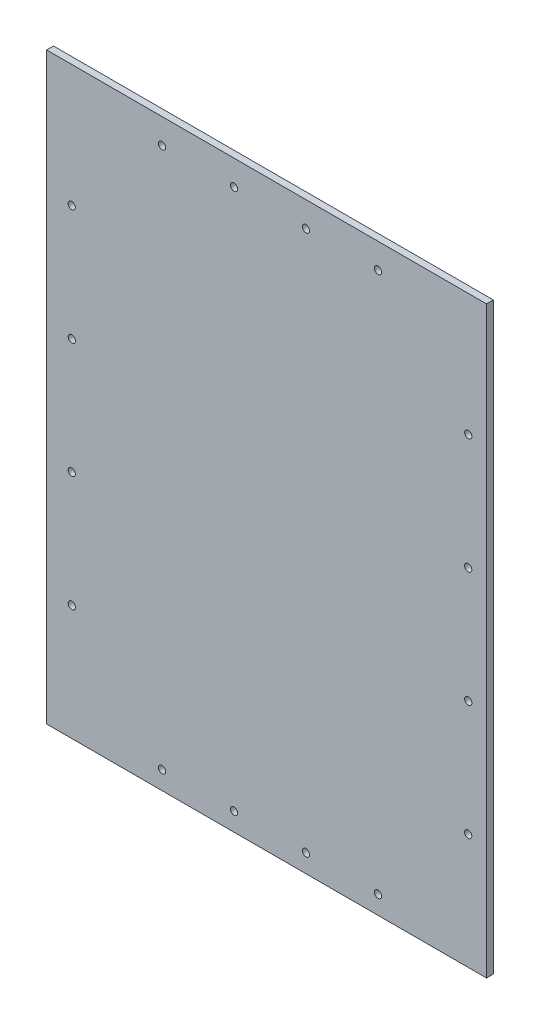
SolidWorks part; units mm, degrees
ref_plane "前基準面" through (0, 0, 0) normal (0, 0, 1) x (1, 0, 0)
ref_plane "上基準面" through (0, 0, 0) normal (0, 1, 0) x (1, 0, 0)
ref_plane "右基準面" through (0, 0, 0) normal (1, 0, 0) x (0, 0, -1)
sketch "草圖1" plane through (0, 0, 0) normal (0, 0, 1) x (1, 0, 0)
  line L1 (152.775, -202.775) -> (-152.775, -202.775)
  line L2 (152.775, -202.775) -> (152.775, 202.775)
  line L3 (152.775, 202.775) -> (-152.775, 202.775)
  line L4 (-152.775, -202.775) -> (-152.775, 202.775)
  line L5 (152.775, -202.775) -> (-152.775, 202.775) construction
  line L6 (152.775, 202.775) -> (-152.775, -202.775) construction
  point P0 (0, 0)
  dimension "D1" = 305.55
  dimension "D2" = 405.55
extrude "填料-伸長1" add sketch "草圖1" along normal blind 4.75
sketch "草圖3" plane through (0, 0, 4.75) normal (0, 0, 1) x (1, 0, 0)
  line L0 (152.775, 202.775) -> (140.075, 202.775) construction
  line L1 (152.775, 202.775) -> (-152.775, 202.775) construction
  line L2 (140.075, 202.775) -> (140.075, 198.025) construction
  line L3 (140.075, 198.025) -> (140.075, 117.865) construction
  line L4 (140.075, 117.865) -> (140.075, 37.705) construction
  line L5 (140.075, 37.705) -> (140.075, -42.455) construction
  line L6 (140.075, -42.455) -> (140.075, -122.615) construction
  circle A0 centre (140.075, 37.705) radius 2.5
  circle A1 centre (140.075, 117.865) radius 2.5
  circle A2 centre (140.075, -42.455) radius 2.5
  circle A3 centre (140.075, -122.615) radius 2.5
  dimension "D7" = 5
  dimension "D8" = 5
  dimension "D9" = 5
  dimension "D10" = 5
  dimension "D1" = 12.7
  dimension "D2" = 4.75
  dimension "D3" = 80.16
  dimension "D4" = 80.16
  dimension "D5" = 80.16
  dimension "D6" = 80.16
extrude "除料-伸長1" cut sketch "草圖3" against normal blind 10
sketch "草圖5" plane through (0, 0, 4.75) normal (0, 0, 1) x (1, 0, 0)
  line L0 (-152.775, 202.775) -> (-148.025, 202.775) construction
  line L1 (152.775, 202.775) -> (-152.775, 202.775) construction
  line L2 (-148.025, 202.775) -> (-135.325, 202.775) construction
  line L3 (-135.325, 202.775) -> (-135.325, 198.025) construction
  line L4 (-135.325, 198.025) -> (-135.325, 117.865) construction
  line L5 (-135.325, 117.865) -> (-135.325, 37.705) construction
  line L6 (-135.325, 37.705) -> (-135.325, -42.455) construction
  line L7 (-135.325, -42.455) -> (-135.325, -122.615) construction
  circle A0 centre (-135.325, -122.615) radius 2.5
  circle A1 centre (-135.325, -42.455) radius 2.5
  circle A2 centre (-135.325, 37.705) radius 2.5
  circle A3 centre (-135.325, 117.865) radius 2.5
  dimension "D8" = 5
  dimension "D9" = 5
  dimension "D10" = 5
  dimension "D11" = 5
  dimension "D1" = 4.75
  dimension "D2" = 12.7
  dimension "D3" = 4.75
  dimension "D4" = 80.16
  dimension "D5" = 80.16
  dimension "D6" = 80.16
  dimension "D7" = 80.16
extrude "除料-伸長3" cut sketch "草圖5" against normal blind 10
sketch "草圖6" plane through (0, 0, 0) normal (0, 0, -1) x (-1, 0, 0)
  line L0 (-152.775, 202.775) -> (-127.375, 202.775) construction
  line L1 (-152.775, 202.775) -> (152.775, 202.775) construction
  line L2 (-127.375, 202.775) -> (-127.375, 190.075) construction
  line L3 (-127.375, 190.075) -> (-127.375, 185.325) construction
  line L4 (-127.375, 185.325) -> (-77.375, 185.325) construction
  line L5 (-77.375, 185.325) -> (-27.375, 185.325) construction
  line L6 (-27.375, 185.325) -> (22.625, 185.325) construction
  line L7 (22.625, 185.325) -> (72.625, 185.325) construction
  circle A0 centre (22.625, 185.325) radius 2.5
  circle A1 centre (72.625, 185.325) radius 2.5
  circle A2 centre (-77.375, 185.325) radius 2.5
  circle A3 centre (-27.375, 185.325) radius 2.5
  dimension "D8" = 5
  dimension "D9" = 5
  dimension "D10" = 5
  dimension "D11" = 5
  dimension "D1" = 25.4
  dimension "D2" = 12.7
  dimension "D3" = 4.75
  dimension "D4" = 50
  dimension "D5" = 50
  dimension "D6" = 50
  dimension "D7" = 50
extrude "除料-伸長4" cut sketch "草圖6" against normal blind 10
sketch "草圖7" plane through (0, 0, 0) normal (0, 0, -1) x (-1, 0, 0)
  line L0 (-152.775, -202.775) -> (-152.775, -190.075) construction
  line L1 (-152.775, -202.775) -> (-152.775, 202.775) construction
  line L2 (-152.775, -190.075) -> (-127.375, -190.075) construction
  line L3 (-127.375, -190.075) -> (-77.375, -190.075) construction
  line L4 (-77.375, -190.075) -> (-27.375, -190.075) construction
  line L5 (-27.375, -190.075) -> (22.625, -190.075) construction
  line L6 (22.625, -190.075) -> (72.625, -190.075) construction
  circle A0 centre (-77.375, -190.075) radius 2.5
  circle A1 centre (-27.375, -190.075) radius 2.5
  circle A2 centre (22.625, -190.075) radius 2.5
  circle A3 centre (72.625, -190.075) radius 2.5
  dimension "D7" = 5
  dimension "D8" = 5
  dimension "D9" = 5
  dimension "D10" = 5
  dimension "D1" = 12.7
  dimension "D2" = 25.4
  dimension "D3" = 50
  dimension "D4" = 50
  dimension "D5" = 50
  dimension "D6" = 50
extrude "除料-伸長5" cut sketch "草圖7" against normal blind 10
